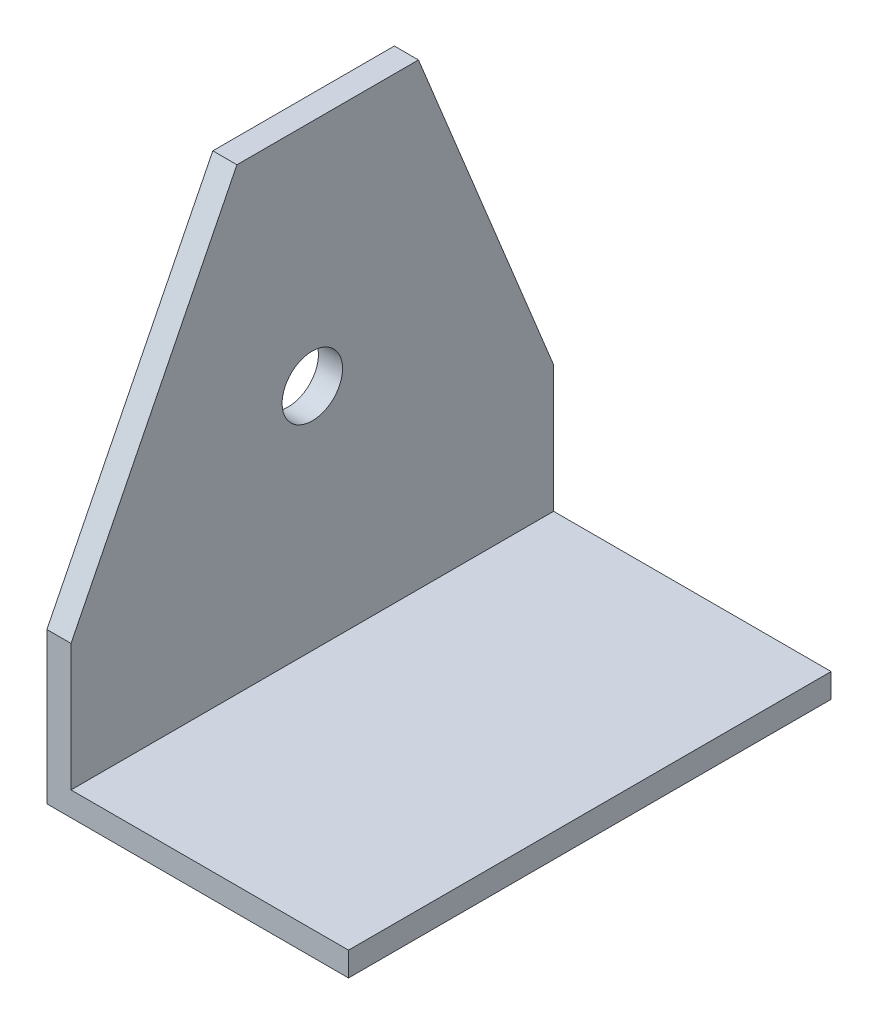
SolidWorks part; units mm, degrees
material "1060 Alloy"
ref_plane "Front Plane" through (0, 0, 0) normal (0, 0, 1) x (1, 0, 0)
ref_plane "Top Plane" through (0, 0, 0) normal (0, 1, 0) x (1, 0, 0)
ref_plane "Right Plane" through (0, 0, 0) normal (1, 0, 0) x (0, 0, -1)
sketch "Sketch1" plane through (0, 0, 0) normal (0, 0, 1) x (1, 0, 0)
  line L0 (-42.9135, 50.7) -> (-42.9135, -29.3)
  line L1 (-42.9135, -29.3) -> (7.0865, -29.3)
  line L2 (7.0865, -29.3) -> (7.0865, -25.3)
  line L3 (7.0865, -25.3) -> (-38.9135, -25.3)
  line L4 (-38.9135, -25.3) -> (-38.9135, 50.7)
  line L5 (-38.9135, 50.7) -> (-42.9135, 50.7)
  dimension "D1" = 4
  dimension "D2" = 50
  dimension "D3" = 80
extrude "Boss-Extrude1" add sketch "Sketch1" along normal blind 80
sketch "Sketch2" plane through (-38.9135, 0, 0) normal (1, 0, 0) x (0, 0, -1)
  line L0 (-80, 50.7) -> (0, 50.7) construction
  line L1 (-80, -25.3) -> (-80, 50.7) construction
  line L2 (0, -25.3) -> (0, 50.7) construction
  circle A0 centre (-40, 12.7) radius 5.0115
  dimension "D1" = 10.023
  dimension "D2" = 38
  dimension "D3" = 80
extrude "Cut-Extrude1" cut sketch "Sketch2" against normal blind 80
sketch "Sketch3" plane through (0, 0, 0) normal (1, 0, 0) x (0, 0, -1)
  line L0 (-80, -4.2672) -> (-52.498, 50.7)
  line L1 (-80, 50.7) -> (-80, -29.3) construction
  line L2 (-80, 50.7) -> (0, 50.7) construction
  line L3 (-52.498, 50.7) -> (-80, 50.7)
  line L4 (-80, 50.7) -> (-80, -4.2672)
  line L5 (0, -4.2672) -> (-22.4007, 50.7)
  line L6 (0, 50.7) -> (0, -29.3) construction
  line L7 (-22.4007, 50.7) -> (0, 50.7)
  line L8 (0, 50.7) -> (0, -4.2672)
extrude "Cut-Extrude2" cut sketch "Sketch3" against normal blind 80
